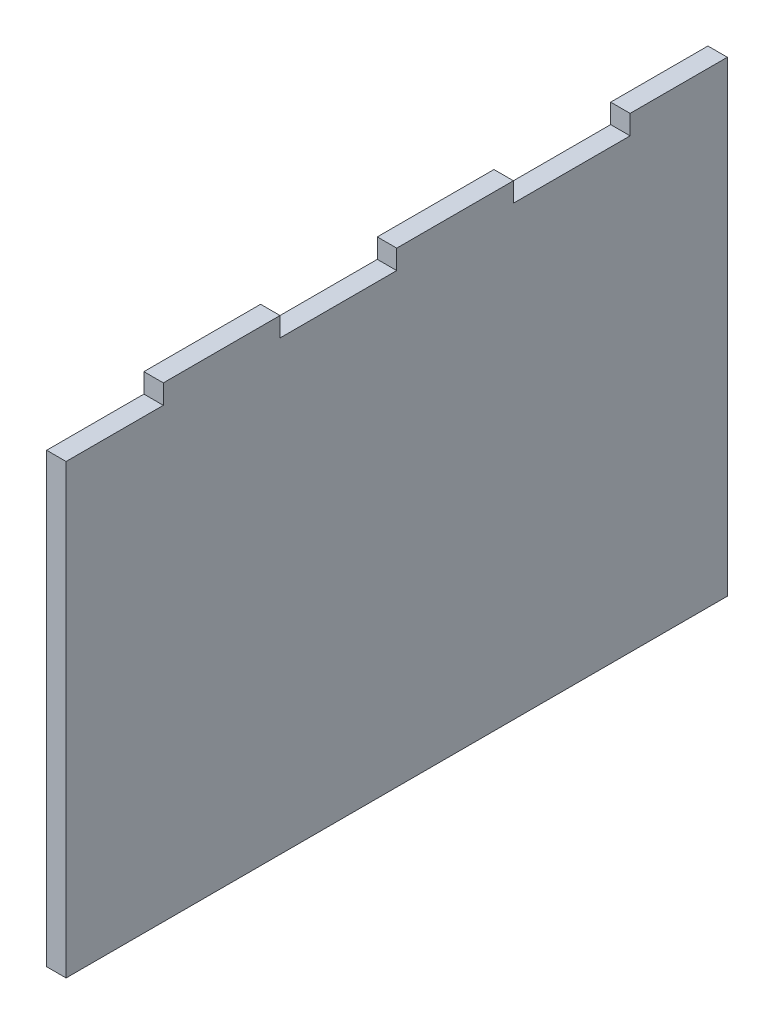
SolidWorks part; units mm, degrees
ref_plane "Front Plane" through (0, 0, 0) normal (0, 0, 1) x (1, 0, 0)
ref_plane "Top Plane" through (0, 0, 0) normal (0, 1, 0) x (1, 0, 0)
ref_plane "Right Plane" through (0, 0, 0) normal (1, 0, 0) x (0, 0, -1)
sketch "Sketch1" plane through (0, 0, 0) normal (1, 0, 0) x (0, 0, -1)
  line L1 (215.9, 152.4) -> (-215.9, 152.4)
  line L2 (215.9, 152.4) -> (215.9, -152.4)
  line L3 (215.9, -152.4) -> (-215.9, -152.4)
  line L4 (-215.9, 152.4) -> (-215.9, -152.4)
  line L5 (215.9, 152.4) -> (-215.9, -152.4) construction
  line L6 (215.9, -152.4) -> (-215.9, 152.4) construction
  point P0 (0, 0)
  dimension "D1" = 304.8
  dimension "D2" = 431.8
extrude "Boss-Extrude1" add sketch "Sketch1" along normal blind 12.7 contours L1 L4 L3 L2
sketch "Sketch2" plane through (12.7, 0, 0) normal (1, 0, 0) x (0, 0, -1)
  line L0 (-215.9, 139.7) -> (215.9, 139.7) construction
  line L1 (-215.9, 152.4) -> (-215.9, -152.4) construction
  line L2 (215.9, 152.4) -> (215.9, -152.4) construction
  line L3 (215.9, 152.4) -> (-215.9, 152.4) construction
  line L4 (-215.9, 152.4) -> (-152.4, 152.4)
  line L5 (-215.9, 152.4) -> (-215.9, 139.7)
  line L6 (-215.9, 139.7) -> (-152.4, 139.7)
  line L7 (-152.4, 152.4) -> (-152.4, 139.7)
  line L8 (-76.2, 152.4) -> (0, 152.4)
  line L9 (-76.2, 152.4) -> (-76.2, 139.7)
  line L10 (-76.2, 139.7) -> (0, 139.7)
  line L11 (0, 152.4) -> (0, 139.7)
  line L13 (76.2, 152.4) -> (152.4, 152.4)
  line L14 (76.2, 152.4) -> (76.2, 139.7)
  line L15 (76.2, 139.7) -> (152.4, 139.7)
  line L16 (152.4, 152.4) -> (152.4, 139.7)
  dimension "D1" = 12.7
  dimension "D2" = 63.5
  dimension "D3" = 76.2
  dimension "D4" = 76.2
  dimension "D5" = 76.2
  dimension "D6" = 76.2
extrude "Cut-Extrude1" cut sketch "Sketch2" against normal through all
